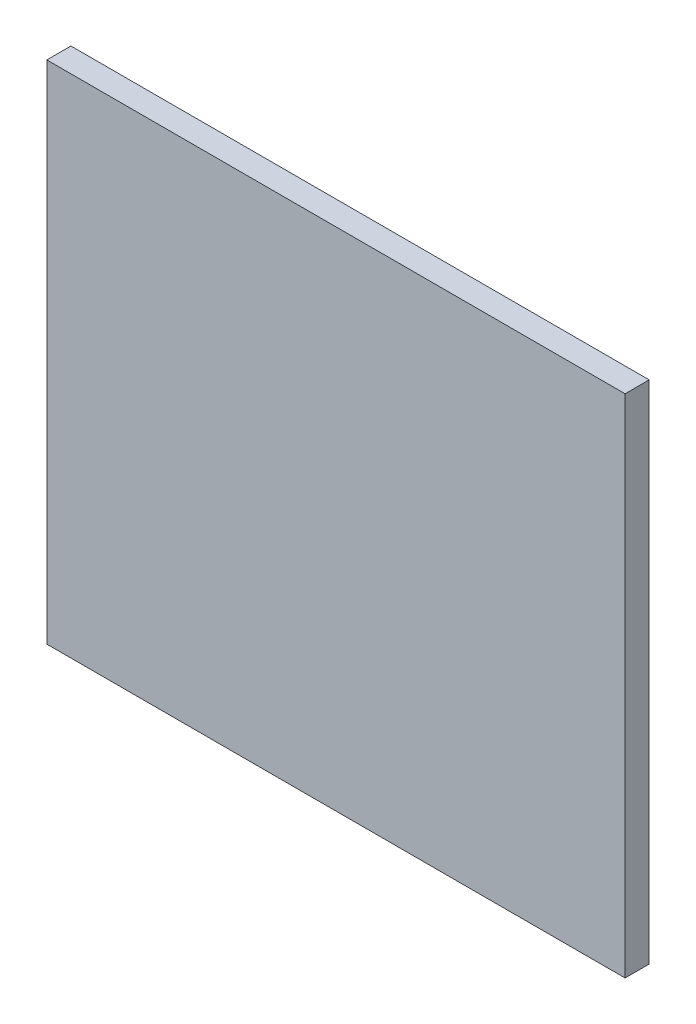
SolidWorks part; units mm, degrees
ref_plane "Alzado" through (0, 0, 0) normal (0, 0, 1) x (1, 0, 0)
ref_plane "Planta" through (0, 0, 0) normal (0, 1, 0) x (1, 0, 0)
ref_plane "Vista lateral" through (0, 0, 0) normal (1, 0, 0) x (0, 0, -1)
sketch "Croquis1" plane through (0, 0, 0) normal (0, 0, 1) x (1, 0, 0)
  line L1 (0, 0) -> (240, 0)
  line L2 (240, 0) -> (240, 210)
  line L3 (240, 210) -> (0, 210)
  line L4 (0, 210) -> (0, 0)
extrude "Saliente-Extruir1" add sketch "Croquis1" along normal blind 10
